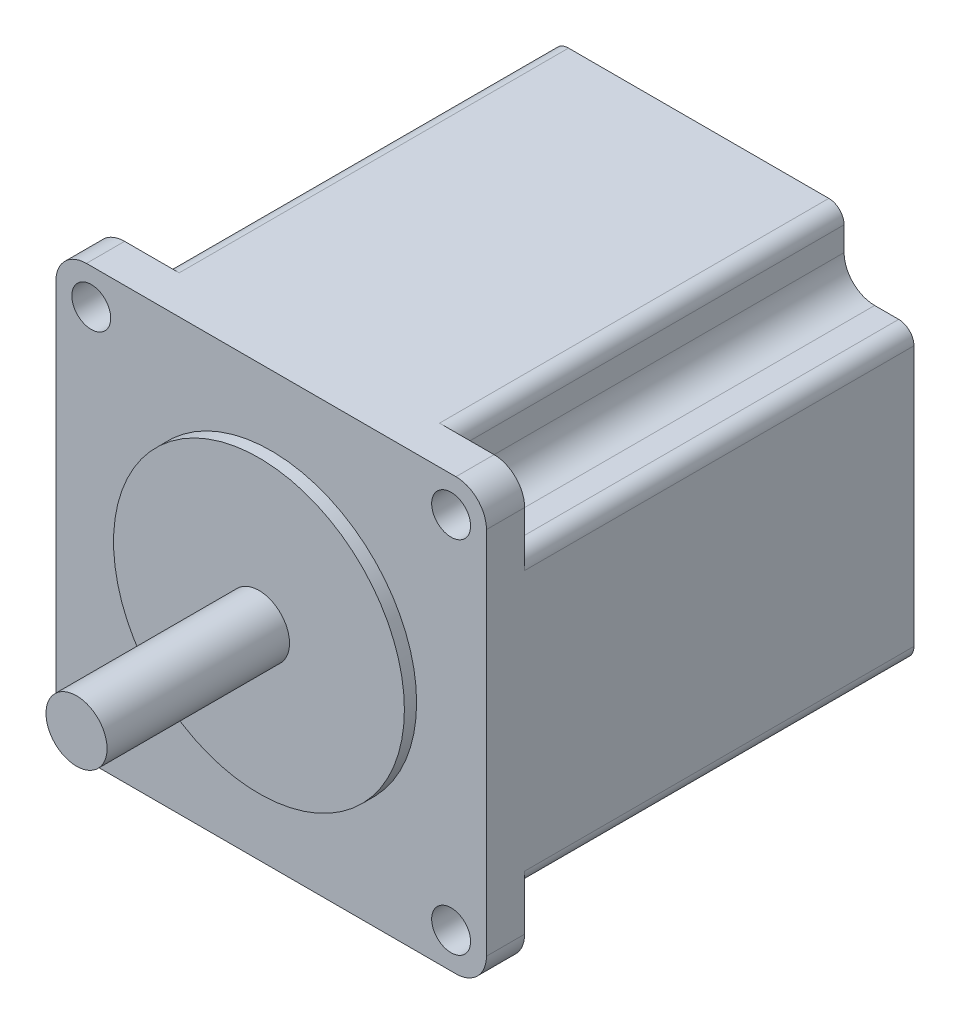
SolidWorks part; units mm, degrees
ref_plane "Front Plane" through (0, 0, 0) normal (0, 0, 1) x (1, 0, 0)
ref_plane "Top Plane" through (0, 0, 0) normal (0, 1, 0) x (1, 0, 0)
ref_plane "Right Plane" through (0, 0, 0) normal (1, 0, 0) x (0, 0, -1)
sketch "Sketch1" plane through (0, 0, 0) normal (0, 0, 1) x (1, 0, 0)
  line L1 (-28.2, 28.2) -> (28.2, 28.2)
  line L2 (-28.2, 28.2) -> (-28.2, -28.2)
  line L3 (-28.2, -28.2) -> (28.2, -28.2)
  line L4 (28.2, 28.2) -> (28.2, -28.2)
  line L5 (-28.2, 28.2) -> (28.2, -28.2) construction
  line L6 (-28.2, -28.2) -> (28.2, 28.2) construction
  point P0 (0, 0)
  dimension "D1" = 56.4
extrude "Boss-Extrude1" add sketch "Sketch1" against normal blind 56
sketch "Sketch2" plane through (0, 0, 0) normal (0, 0, 1) x (1, 0, 0)
  line L1 (-23.57, 23.57) -> (23.57, 23.57) construction
  line L2 (-23.57, 23.57) -> (-23.57, -23.57) construction
  line L3 (-23.57, -23.57) -> (23.57, -23.57) construction
  line L4 (23.57, 23.57) -> (23.57, -23.57) construction
  line L5 (-23.57, 23.57) -> (23.57, -23.57) construction
  line L6 (-23.57, -23.57) -> (23.57, 23.57) construction
  circle A0 centre (-23.57, 23.57) radius 2.55
  circle A1 centre (23.57, 23.57) radius 2.55
  circle A2 centre (23.57, -23.57) radius 2.55
  circle A3 centre (-23.57, -23.57) radius 2.55
  point P0 (0, 0)
  dimension "D2" = 5.1
  dimension "D1" = 47.14
extrude "Cut-Extrude1" cut sketch "Sketch2" against normal blind 6
sketch "Sketch3" plane through (0, 0, 0) normal (0, 0, 1) x (1, 0, 0)
  circle A0 centre (0, 0) radius 19.05
  dimension "D1" = 38.1
extrude "Boss-Extrude2" add sketch "Sketch3" along normal blind 1.6
sketch "Sketch4" plane through (0, 0, 1.6) normal (0, 0, 1) x (1, 0, 0)
  circle A0 centre (0, 0) radius 4
  dimension "D1" = 8
extrude "Boss-Extrude3" add sketch "Sketch4" along normal offset from surface (23.9 mm away) 25.5 up to face at (19.05, 0, 0) offset beyond the face yes
fillet "Fillet1" radius 4 4 edges at (-28.2, -28.2, -28) (28.2, -28.2, -28) (28.2, 28.2, -28) (-28.2, 28.2, -28)
sketch "Sketch5" plane through (0, 0, -56) normal (0, 0, -1) x (-1, 0, 0)
  line L20 (0, 0) -> (0, 19.05) construction
  line L21 (0, 0) -> (19.05, 0) construction
  line L22 (0, -19.05) -> (0, 0) construction
  line L23 (0, 0) -> (-19.05, 0) construction
  line L24 (-24.2, 28.2) -> (24.2, 28.2) construction
  line L26 (-19.05, 28.2) -> (-28.2, 28.2)
  line L27 (-19.05, 28.2) -> (-19.05, 19.05)
  line L28 (-19.05, 19.05) -> (-28.2, 19.05)
  line L29 (-28.2, 28.2) -> (-28.2, 19.05)
  line L30 (-28.2, -24.2) -> (-28.2, 24.2) construction
  line L31 (28.2, 28.2) -> (28.2, 19.05)
  line L32 (19.05, 19.05) -> (28.2, 19.05)
  line L33 (19.05, 28.2) -> (19.05, 19.05)
  line L34 (19.05, 28.2) -> (28.2, 28.2)
  line L35 (19.05, -28.2) -> (28.2, -28.2)
  line L36 (19.05, -28.2) -> (19.05, -19.05)
  line L37 (19.05, -19.05) -> (28.2, -19.05)
  line L38 (28.2, -28.2) -> (28.2, -19.05)
  line L39 (-28.2, -28.2) -> (-28.2, -19.05)
  line L40 (-19.05, -19.05) -> (-28.2, -19.05)
  line L41 (-19.05, -28.2) -> (-19.05, -19.05)
  line L42 (-19.05, -28.2) -> (-28.2, -28.2)
  line L43 (-19.05, 19.05) -> (19.05, 19.05) construction
  line L44 (19.05, 19.05) -> (19.05, -19.05) construction
  line L45 (19.05, -19.05) -> (-19.05, -19.05) construction
  line L46 (-19.05, 19.05) -> (-19.05, -19.05) construction
  circle A1 centre (0, 0) radius 19.05 construction
extrude "Cut-Extrude2" cut sketch "Sketch5" against normal offset from surface (51 mm away) 5 up to face at (19.05, 0, 0)
fillet "Fillet3" radius 4 4 edges at (19.05, -19.05, -30.5) (-19.05, -19.05, -30.5) (-19.05, 19.05, -30.5) (19.05, 19.05, -30.5)
fillet "Fillet4" radius 2 8 edges at (-19.05, 28.2, -30.5) (-28.2, 19.05, -30.5) (-28.2, -19.05, -30.5) (-19.05, -28.2, -30.5) (19.05, -28.2, -30.5) (28.2, -19.05, -30.5) (28.2, 19.05, -30.5) (19.05, 28.2, -30.5)
